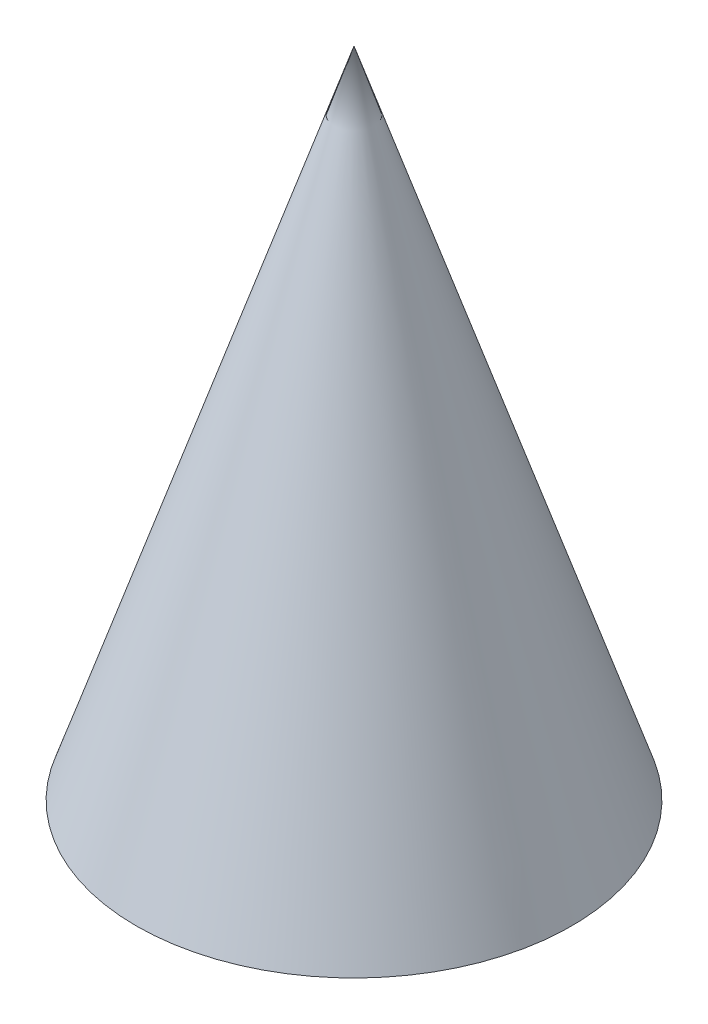
SolidWorks part; units mm, degrees
ref_plane "前视基准面" through (0, 0, 0) normal (0, 0, 1) x (1, 0, 0)
ref_plane "上视基准面" through (0, 0, 0) normal (0, 1, 0) x (1, 0, 0)
ref_plane "右视基准面" through (0, 0, 0) normal (1, 0, 0) x (0, 0, -1)
sketch "草图1" plane through (0, 0, 0) normal (0, 0, 1) x (1, 0, 0)
  line L0 (0, 0) -> (25, 0)
  line L1 (0, 0) -> (0, 75)
  line L2 (0, 75) -> (25, 0)
revolve "旋转1" add sketch "草图1" angle 360 about L1
